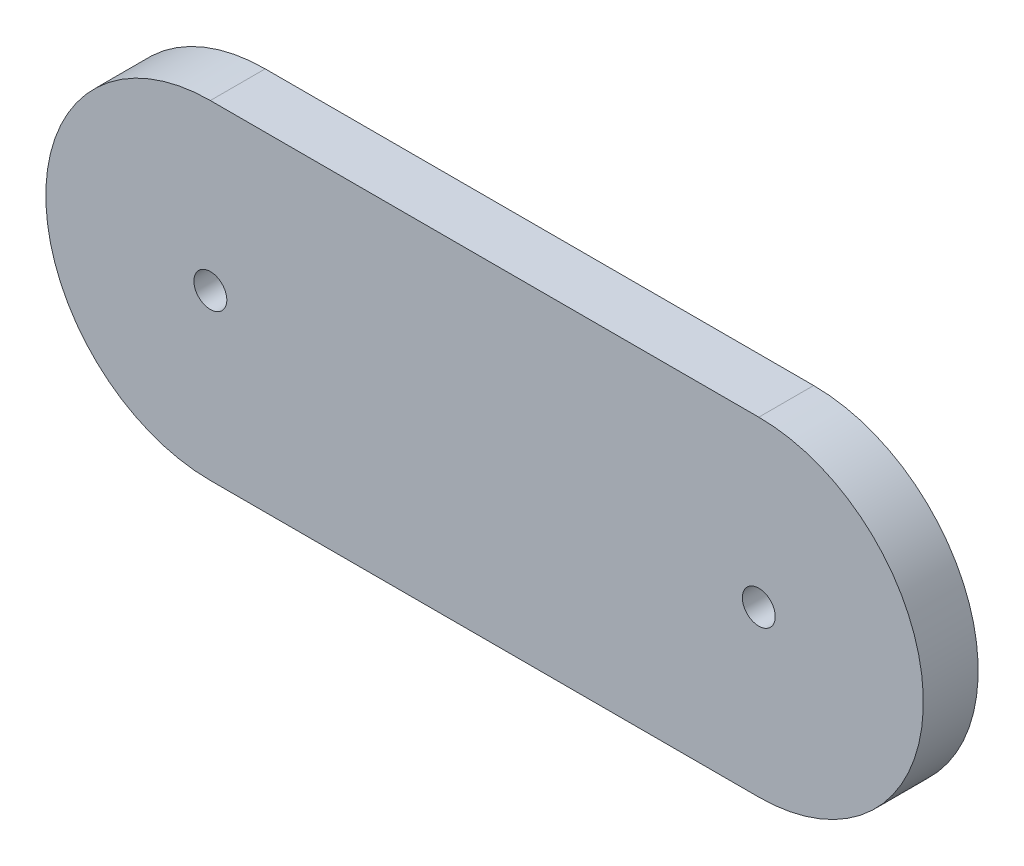
SolidWorks part; units mm, degrees
material "PVC 0.007 Plasticized"
ref_plane "Front Plane" through (0, 0, 0) normal (0, 0, 1) x (1, 0, 0)
ref_plane "Top Plane" through (0, 0, 0) normal (0, 1, 0) x (1, 0, 0)
ref_plane "Right Plane" through (0, 0, 0) normal (1, 0, 0) x (0, 0, -1)
sketch "Sketch1" plane through (0, 0, 0) normal (0, 0, 1) x (1, 0, 0)
  line L0 (0, 0) -> (50, 0)
  dimension "D1" = 50
sketch "Sketch2" plane through (0, 0, 0) normal (0, 0, 1) x (1, 0, 0)
  line L0 (0, 15) -> (50, 15)
  line L1 (0, -15) -> (50, -15)
  arc A0 (0, 15) -> (0, -15) centre (0, 0) ccw
  arc A1 (50, -15) -> (50, 15) centre (50, 0) ccw
  dimension "D1" = 30
  dimension "D2" = 30
extrude "Boss-Extrude1" add sketch "Sketch2" along normal blind 5
sketch "Sketch3" plane through (0, 0, 0) normal (0, 0, -1) x (-1, 0, 0)
  circle A0 centre (-50, 0) radius 1.5
  circle A1 centre (0, 0) radius 1.5
  dimension "D1" = 3
  dimension "D2" = 3
extrude "Cut-Extrude1" cut sketch "Sketch3" against normal blind 5
